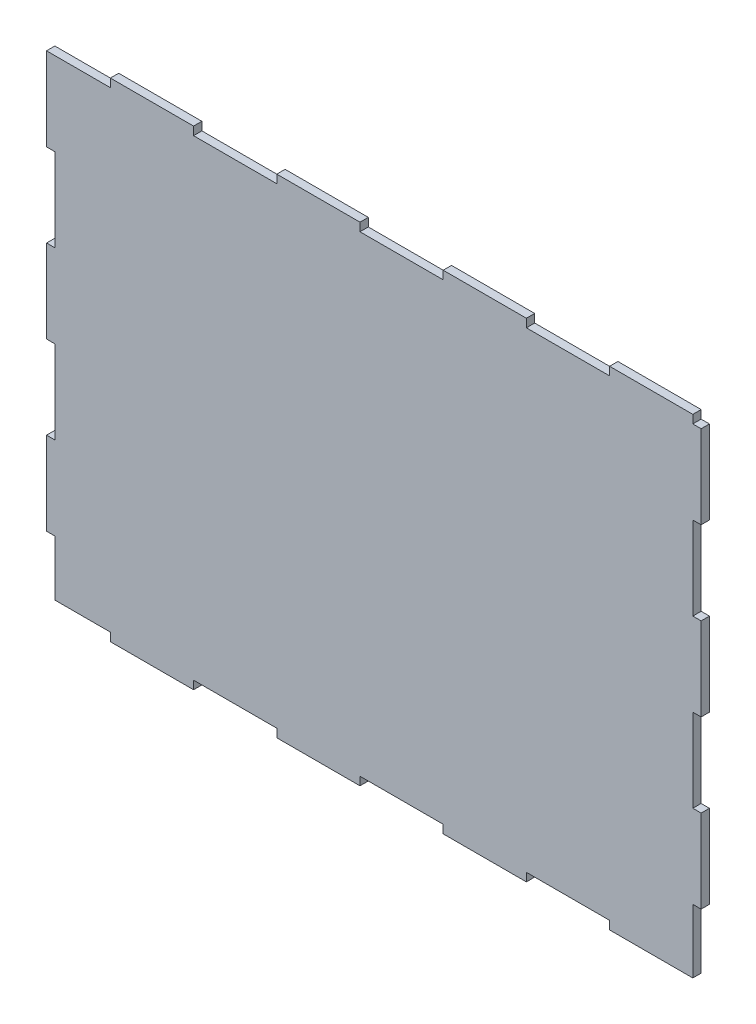
SolidWorks part; units mm, degrees
ref_plane "Plan de face" through (0, 0, 0) normal (0, 0, 1) x (1, 0, 0)
ref_plane "Plan de dessus" through (0, 0, 0) normal (0, 1, 0) x (1, 0, 0)
ref_plane "Plan de droite" through (0, 0, 0) normal (1, 0, 0) x (0, 0, -1)
sketch "Esquisse1" plane through (0, 0, 0) normal (0, 0, 1) x (1, 0, 0)
  line L1 (-85.4628, 61.9231) -> (144.5372, 61.9231)
  line L2 (-85.4628, 61.9231) -> (-85.4628, -108.0769)
  line L3 (-85.4628, -108.0769) -> (144.5372, -108.0769)
  line L4 (144.5372, 61.9231) -> (144.5372, -108.0769)
  dimension "D1" = 230
  dimension "D3" = 170
extrude "Boss.-Extru.1" add sketch "Esquisse1" along normal blind 3
sketch "Esquisse2" plane through (0, 0, 0) normal (0, 0, -1) x (-1, 0, 0)
  line L0 (-144.5372, 63.4231) -> (85.4434, 63.4231) construction
  line L1 (-144.5372, 61.9231) -> (-114.5372, 61.9231)
  line L2 (-144.5372, 61.9231) -> (-144.5372, 64.9231)
  line L3 (-144.5372, 64.9231) -> (-114.5372, 64.9231)
  line L4 (-114.5372, 61.9231) -> (-114.5372, 64.9231)
  line L5 (-84.5372, 61.9231) -> (-54.5372, 61.9231)
  line L6 (-54.5372, 61.9231) -> (-54.5372, 64.9231)
  line L7 (-84.5372, 63.4231) -> (145.4434, 63.4231) construction
  line L8 (-24.5372, 61.9231) -> (5.4628, 61.9231)
  line L9 (5.4628, 61.9231) -> (5.4628, 64.9231)
  line L10 (-24.5372, 63.4231) -> (205.4434, 63.4231) construction
  line L11 (35.4628, 61.9231) -> (65.4628, 61.9231)
  line L12 (65.4628, 61.9231) -> (65.4628, 64.9231)
  line L13 (35.4628, 63.4231) -> (265.4434, 63.4231) construction
  line L14 (-54.5372, 64.9231) -> (-84.5372, 64.9231)
  line L15 (-84.5372, 61.9231) -> (-84.5372, 64.9231)
  line L16 (5.4628, 64.9231) -> (-24.5372, 64.9231)
  line L17 (-24.5372, 61.9231) -> (-24.5372, 64.9231)
  line L18 (35.4628, 61.9231) -> (35.4628, 64.9231)
  line L19 (35.4628, 64.9231) -> (65.4628, 64.9231)
  line L20 (-144.5372, -23.0769) -> (85.4628, -23.0769) construction
  line L21 (-144.5372, -108.0769) -> (-144.5372, 61.9231) construction
  line L22 (85.4628, 61.9231) -> (85.4628, -108.0769) construction
  line L23 (35.4628, -108.0769) -> (65.4628, -108.0769)
  line L24 (65.4628, -108.0769) -> (65.4628, -111.0769)
  line L25 (-144.5372, -111.0769) -> (-114.5372, -111.0769)
  line L26 (-114.5372, -108.0769) -> (-114.5372, -111.0769)
  line L27 (-144.5372, -108.0769) -> (-114.5372, -108.0769)
  line L28 (-144.5372, -108.0769) -> (-144.5372, -111.0769)
  line L29 (-84.5372, -108.0769) -> (-54.5372, -108.0769)
  line L30 (-54.5372, -108.0769) -> (-54.5372, -111.0769)
  line L31 (-54.5372, -111.0769) -> (-84.5372, -111.0769)
  line L32 (-84.5372, -108.0769) -> (-84.5372, -111.0769)
  line L33 (-24.5372, -108.0769) -> (5.4628, -108.0769)
  line L34 (5.4628, -108.0769) -> (5.4628, -111.0769)
  line L35 (5.4628, -111.0769) -> (-24.5372, -111.0769)
  line L36 (-24.5372, -108.0769) -> (-24.5372, -111.0769)
  line L37 (35.4628, -108.0769) -> (35.4628, -111.0769)
  line L38 (35.4628, -111.0769) -> (65.4628, -111.0769)
  dimension "D1" = 3
  dimension "D2" = 30
  dimension "D3" = 4
extrude "Boss.-Extru.6" add sketch "Esquisse2" against normal blind 3
sketch "Esquisse4" plane through (0, 0, 0) normal (0, 0, -1) x (-1, 0, 0)
  line L0 (86.9628, 61.9231) -> (86.9628, -108.0769) construction
  line L1 (85.4628, 61.9231) -> (88.4628, 61.9231)
  line L2 (85.4628, 61.9231) -> (85.4628, 31.9231)
  line L3 (85.4628, 31.9231) -> (88.4628, 31.9231)
  line L4 (88.4628, 61.9231) -> (88.4628, 31.9231)
  line L5 (86.9628, 1.9231) -> (86.9628, -168.0769) construction
  line L6 (85.4628, 1.9231) -> (85.4628, -28.0769)
  line L7 (85.4628, 1.9231) -> (88.4628, 1.9231)
  line L8 (88.4628, 1.9231) -> (88.4628, -28.0769)
  line L9 (85.4628, -28.0769) -> (88.4628, -28.0769)
  line L10 (86.9628, -58.0769) -> (86.9628, -228.0769) construction
  line L11 (85.4628, -58.0769) -> (85.4628, -88.0769)
  line L12 (85.4628, -58.0769) -> (88.4628, -58.0769)
  line L13 (88.4628, -58.0769) -> (88.4628, -88.0769)
  line L14 (85.4628, -88.0769) -> (88.4628, -88.0769)
  line L15 (-144.5372, -23.0769) -> (85.4628, -23.0769) construction
  line L16 (-144.5372, -111.0769) -> (-144.5372, 64.9231) construction
  line L17 (85.4628, 61.9231) -> (85.4628, -108.0769) construction
  line L18 (85.4628, -23.0769) -> (-29.5372, -23.0769) construction
  line L19 (-29.5372, -23.0769) -> (-29.5372, 61.9231) construction
  line L20 (-54.5372, 61.9231) -> (-24.5372, 61.9231) construction
  line L21 (-29.5372, 61.9231) -> (-29.5372, -108.0769) construction
  line L22 (-24.5372, -108.0769) -> (-54.5372, -108.0769) construction
  line L23 (-144.5372, 31.9231) -> (-147.5372, 31.9231)
  line L24 (-147.5372, 61.9231) -> (-147.5372, 31.9231)
  line L25 (-144.5372, 61.9231) -> (-147.5372, 61.9231)
  line L26 (-144.5372, 61.9231) -> (-144.5372, 31.9231)
  line L27 (-144.5372, 1.9231) -> (-147.5372, 1.9231)
  line L28 (-147.5372, 1.9231) -> (-147.5372, -28.0769)
  line L29 (-144.5372, -28.0769) -> (-147.5372, -28.0769)
  line L30 (-144.5372, 1.9231) -> (-144.5372, -28.0769)
  line L31 (-144.5372, -58.0769) -> (-147.5372, -58.0769)
  line L32 (-147.5372, -58.0769) -> (-147.5372, -88.0769)
  line L33 (-144.5372, -88.0769) -> (-147.5372, -88.0769)
  line L34 (-144.5372, -58.0769) -> (-144.5372, -88.0769)
  point P4 (86.9628, 61.9231)
  point P46 (86.9628, 28.8765)
  dimension "D1" = 30
  dimension "D2" = 3
  dimension "D3" = 3
  dimension "D4" = 3.0466
extrude "Boss.-Extru.7" add sketch "Esquisse4" against normal blind 3
